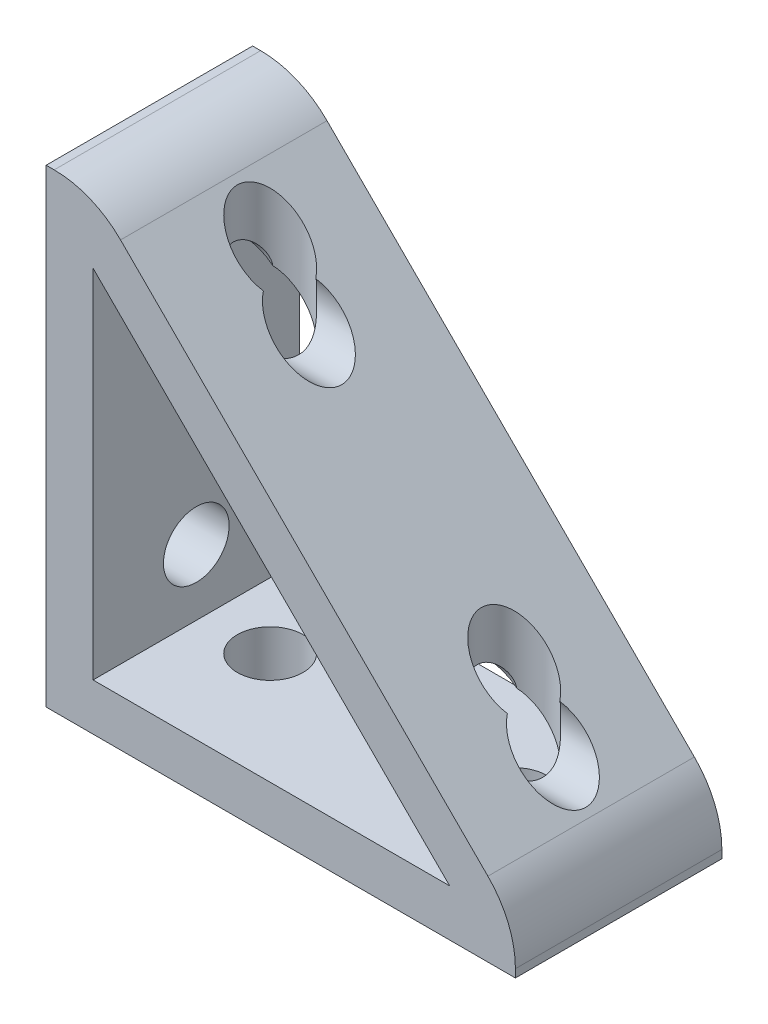
SolidWorks part; units mm, degrees
ref_plane "Front Plane" through (0, 0, 0) normal (0, 0, 1) x (1, 0, 0)
ref_plane "Top Plane" through (0, 0, 0) normal (0, 1, 0) x (1, 0, 0)
ref_plane "Right Plane" through (0, 0, 0) normal (1, 0, 0) x (0, 0, -1)
sketch "Sketch1" plane through (0, 0, 0) normal (0, 0, 1) x (1, 0, 0)
  line L0 (-28.4663, 33.6735) -> (-28.4663, -16.3265)
  line L1 (-28.4663, -16.3265) -> (21.5337, -16.3265)
  line L2 (21.5337, -16.3265) -> (21.5337, -11.3265)
  line L3 (21.5337, -11.3265) -> (-23.4663, 33.6735)
  line L4 (-23.4663, 33.6735) -> (-28.4663, 33.6735)
  line L5 (14.5337, -11.3265) -> (-23.4663, -11.3265)
  line L6 (-23.4663, -11.3265) -> (-23.4663, 26.6735)
  line L7 (-23.4663, 26.6735) -> (14.5337, -11.3265)
  dimension "D1" = 50
  dimension "D2" = 50
  dimension "D3" = 5
  dimension "D4" = 5
  dimension "D5" = 7
  dimension "D6" = 7
extrude "Boss-Extrude1" add sketch "Sketch1" along normal blind 22 contours L6 L7 L5 | L0 L1 L2 L3 L4
fillet "Fillet1" radius 10 1 edges at (-23.4663, 33.6735, 11)
fillet "Fillet2" radius 10 1 edges at (21.5337, -11.3265, 11)
sketch "Sketch2" plane through (-28.4663, 0, 0) normal (-1, 0, 0) x (0, 0, 1)
  line L0 (0, 33.6735) -> (0, -16.3265) construction
  line L1 (22, 33.6735) -> (0, 33.6735) construction
  line L2 (22, -16.3265) -> (0, -16.3265) construction
  circle A0 centre (11, 21.6735) radius 3.5
  circle A1 centre (11, -4.3265) radius 3.5
  dimension "D1" = 7
  dimension "D2" = 7
  dimension "D3" = 11
  dimension "D4" = 11
  dimension "D5" = 12
  dimension "D6" = 12
extrude "Cut-Extrude2" cut sketch "Sketch2" against normal blind 50
sketch "Sketch4" plane through (0, -16.3265, 0) normal (0, -1, 0) x (1, 0, 0)
  line L0 (21.5337, 22) -> (21.5337, 0) construction
  line L1 (-28.4663, 22) -> (-28.4663, 0) construction
  circle A0 centre (-16.4663, 10.1278) radius 3.5
  circle A1 centre (9.5337, 10.1278) radius 3.5
  dimension "D1" = 7
  dimension "D2" = 7
  dimension "D3" = 12
  dimension "D4" = 12
extrude "Cut-Extrude3" cut sketch "Sketch4" against normal blind 50
